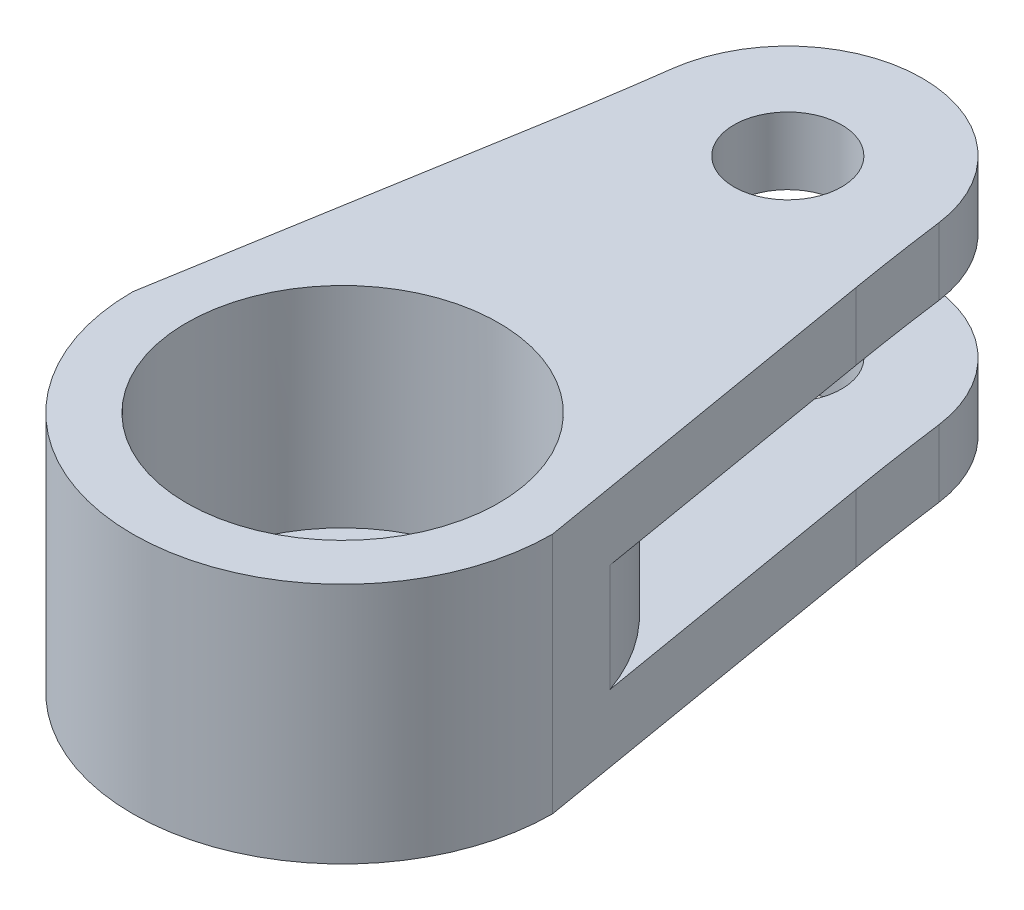
SolidWorks part; units mm, degrees
material "PLA"
ref_plane "Alzado" through (0, 0, 0) normal (0, 0, 1) x (1, 0, 0)
ref_plane "Planta" through (0, 0, 0) normal (0, 1, 0) x (1, 0, 0)
ref_plane "Vista lateral" through (0, 0, 0) normal (1, 0, 0) x (0, 0, -1)
sketch "Croquis1" plane through (0, 0, 0) normal (0, 1, 0) x (1, 0, 0)
  line L0 (0, 0) -> (0, 8.27) construction
  line L1 (-3.9, 0) -> (-2.5, 8.27)
  line L2 (2.5, 8.27) -> (3.9, 0)
  arc A1 (-3.9, 0) -> (3.9, 0) centre (0, 0) ccw
  arc A2 (2.5, 8.27) -> (-2.5, 8.27) centre (0, 8.27) ccw
  dimension "D1" = 8.27
  dimension "D2" = 5
  dimension "D3" = 3.9
extrude "Saliente-Extruir1" add sketch "Croquis1" along normal blind 4.5
sketch "Croquis3" plane through (0, 4.5, 0) normal (0, 1, 0) x (1, 0, 0)
  circle A0 centre (0, 0) radius 2.9
  circle A1 centre (0, 8.27) radius 1
  dimension "D1" = 2
  dimension "D2" = 5.8
extrude "Cortar-Extruir1" cut sketch "Croquis3" against normal through all
sketch "Croquis7" plane through (0, 0, 0) normal (0, -1, 0) x (1, 0, 0)
  circle A0 centre (0, 0) radius 2.9
  circle A1 centre (0, 0) radius 1.5
  dimension "D1" = 5.8
  dimension "D2" = 3
fillet "Redondeo1" radius 50 2 edges at (-2.5, 2.25, -8.27) (2.5, 2.25, -8.27)
sketch "Croquis9" plane through (0, 4.5, 0) normal (0, 1, 0) x (1, 0, 0)
  line L2 (3.9, 0) -> (2.7506, 6.7897)
  line L3 (-2.7506, 6.7897) -> (-3.9, 0)
  line L4 (3.6827, 1.2836) -> (2.7506, 6.7897)
  line L5 (-2.7506, 6.7897) -> (-3.6827, 1.2836)
  arc A0 (3.6827, 1.2836) -> (-3.6827, 1.2836) centre (0, 0) ccw
  circle A1 centre (0, 8.27) radius 1 construction
  circle A2 centre (0, 8.27) radius 1
  arc A5 (-3.9, 0) -> (3.9, 0) centre (0, 0) ccw
  arc A6 (2.4785, 8.5969) -> (2.7506, 6.7897) centre (52.0492, 15.1353) ccw
  arc A7 (2.4785, 8.5969) -> (-2.4785, 8.5969) centre (0, 8.27) ccw
  arc A8 (-2.7506, 6.7897) -> (-2.4785, 8.5969) centre (-52.0492, 15.1353) ccw
  arc A10 (2.4785, 8.5969) -> (2.7506, 6.7897) centre (52.0492, 15.1353) ccw
  arc A11 (2.4785, 8.5969) -> (-2.4785, 8.5969) centre (0, 8.27) ccw
  arc A12 (-2.7506, 6.7897) -> (-2.4785, 8.5969) centre (-52.0492, 15.1353) ccw
  dimension "D1" = 0
extrude "Cortar-Extruir2" cut sketch "Croquis9" against normal mid plane 2 from offset 2.25 offset against normal yes
extrude "Saliente-Extruir2" add sketch "Croquis7" against normal blind 0.6
